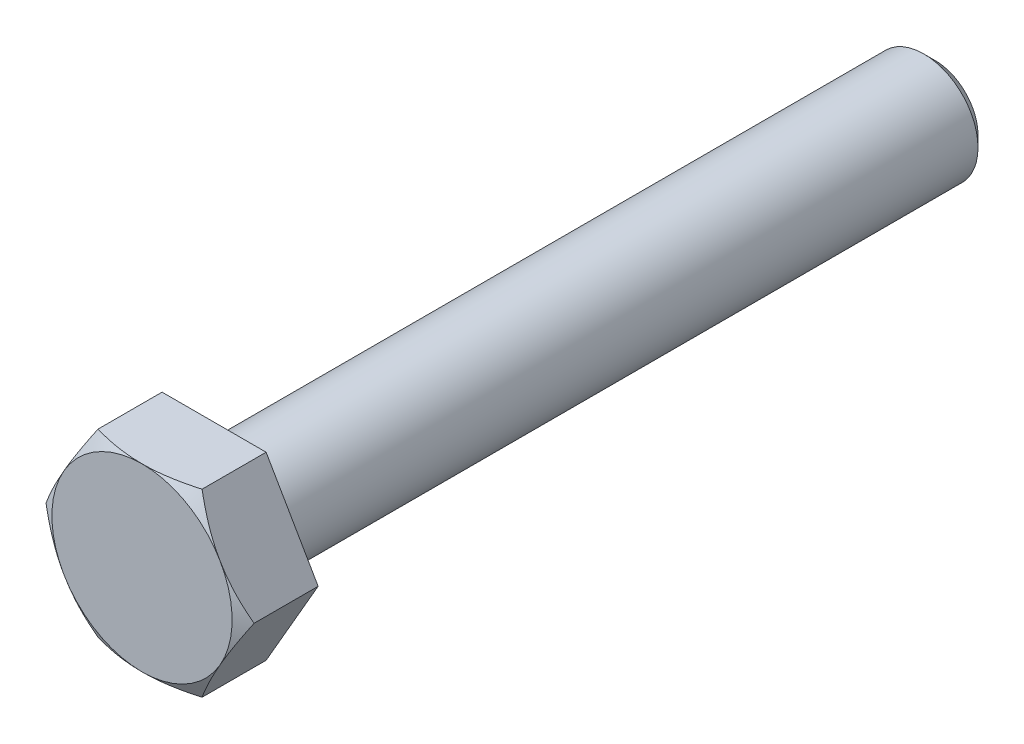
SolidWorks part; units mm, degrees
ref_plane "Plane1" through (0, 0, 0) normal (0, 0, 1) x (1, 0, 0)
ref_plane "MSC_PF1" through (0, 0, 0) normal (0, 1, 0) x (1, 0, 0)
ref_plane "Plane3" through (0, 0, 0) normal (1, 0, 0) x (0, 0, -1)
sketch "Sketch1" plane through (0, 0, 0) normal (0, 0, 1) x (1, 0, 0)
  line L0 (0, 0) -> (1, 0) construction
  line L1 (-2.8868, 5) -> (2.8868, 5)
  line L2 (-2.8868, -5) -> (2.8868, -5)
  line L3 (2.8868, 5) -> (5.7735, 0)
  line L4 (5.7735, 0) -> (2.8868, -5)
  line L5 (-2.8868, 5) -> (-5.7735, 0)
  line L6 (-5.7735, 0) -> (-2.8868, -5)
  circle A0 centre (0, 0) radius 5 construction
  dimension "P" = 1
  dimension "s" = 10
extrude "Base-Extrude" add sketch "Sketch1" along normal blind 4
sketch "Sketch5" plane through (0, 0, 0) normal (0, 1, 0) x (1, 0, 0)
  line L0 (0, 0) -> (0, -62.6881) construction
  line L1 (-5.7735, -4) -> (-5, -4)
  line L2 (-5, -4) -> (-5.7735, -3.5534)
  line L3 (-5.7735, -4) -> (-5.7735, 0) construction
  line L4 (-5.7735, -3.5534) -> (-5.7735, -4)
  dimension "D1" = 30
  dimension "D2" = 5
revolve "Cut-Revolve1" cut sketch "Sketch5" angle 360 about L0
sketch "Sketch3" plane through (0, 0, 0) normal (0, 0, -1) x (-1, 0, 0)
  circle A0 centre (0, 0) radius 3
  dimension "_d" = 6
extrude "Boss-Extrude1" add sketch "Sketch3" along normal blind 40
cosmetic thread "Cosmetic Thread1" parameters "b"=18, "D2"=4.7732
chamfer "Chamfer1" distance 0.6134 angle 45 1 edges at (-3, 0, -40)
fillet "Fillet1" radius 0.25 1 edges at (3, 0, 0)
equation "\"D2@Sketch5\" = \"s@Sketch1\" / 2"
equation "\"D2@Cosmetic Thread1\" = \"_d@Sketch3\" - 2 * 0.6134 * \"P@Sketch1\""
equation "\"D1@Chamfer1\" =  ( \"_d@Sketch3\" - \"D2@Cosmetic Thread1\" )  / 2"
